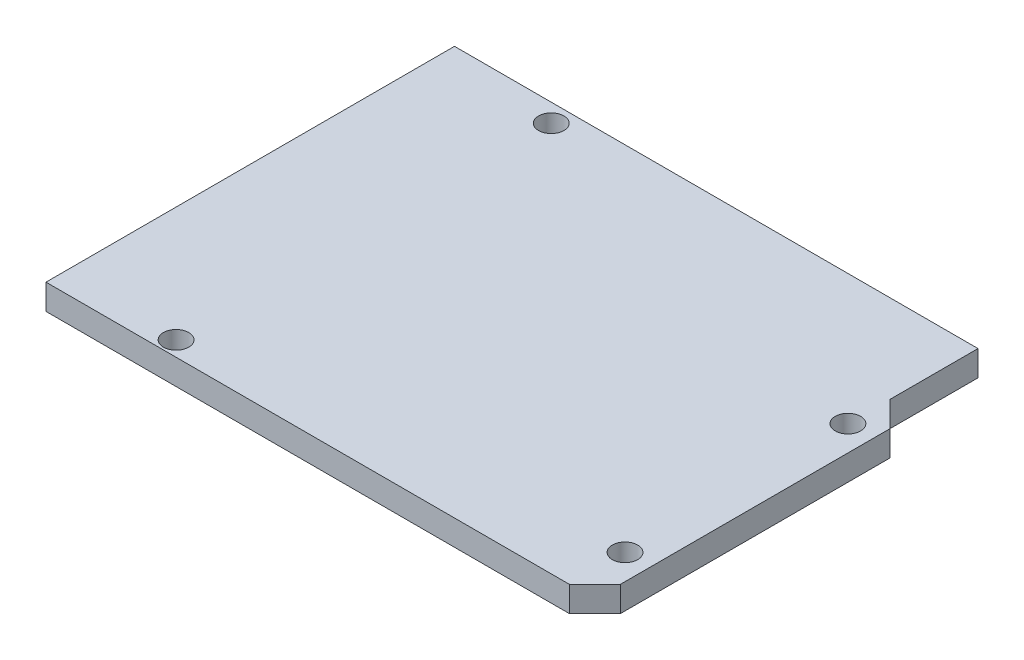
SolidWorks part; units mm, degrees
ref_plane "Alzado" through (0, 0, 0) normal (0, 0, 1) x (1, 0, 0)
ref_plane "Planta" through (0, 0, 0) normal (0, 1, 0) x (1, 0, 0)
ref_plane "Vista lateral" through (0, 0, 0) normal (1, 0, 0) x (0, 0, -1)
sketch "Croquis1" plane through (0, 0, 0) normal (0, 1, 0) x (1, 0, 0)
  line L0 (0, 0) -> (66, 0)
  line L2 (66, 0) -> (69.2, 3.2)
  line L3 (69.2, 3.2) -> (69.2, 37.2)
  line L4 (69.2, 37.2) -> (66, 40.4)
  line L5 (66, 40.4) -> (66, 51.5)
  line L6 (66, 51.5) -> (0, 51.5)
  line L7 (0, 51.5) -> (0, 0)
  circle A0 centre (14.5, 49.2) radius 1.6
  circle A1 centre (14.5, 1.9) radius 1.6
  circle A2 centre (66, 35.1) radius 1.6
  circle A3 centre (66, 7) radius 1.6
  dimension "D6" = 3.2
  dimension "D8" = 3.2
  dimension "D9" = 3.2
  dimension "D10" = 3.2
  dimension "D1" = 51.5
  dimension "D2" = 66
  dimension "D3" = 34
  dimension "D4" = 3.2
  dimension "D5" = 135
  dimension "D7" = 135
  dimension "D11" = 28.1
  dimension "D12" = 7
  dimension "D13" = 14.5
  dimension "D14" = 47.3
  dimension "D15" = 0.3
extrude "Saliente-Extruir1" add sketch "Croquis1" along normal blind 3.2
